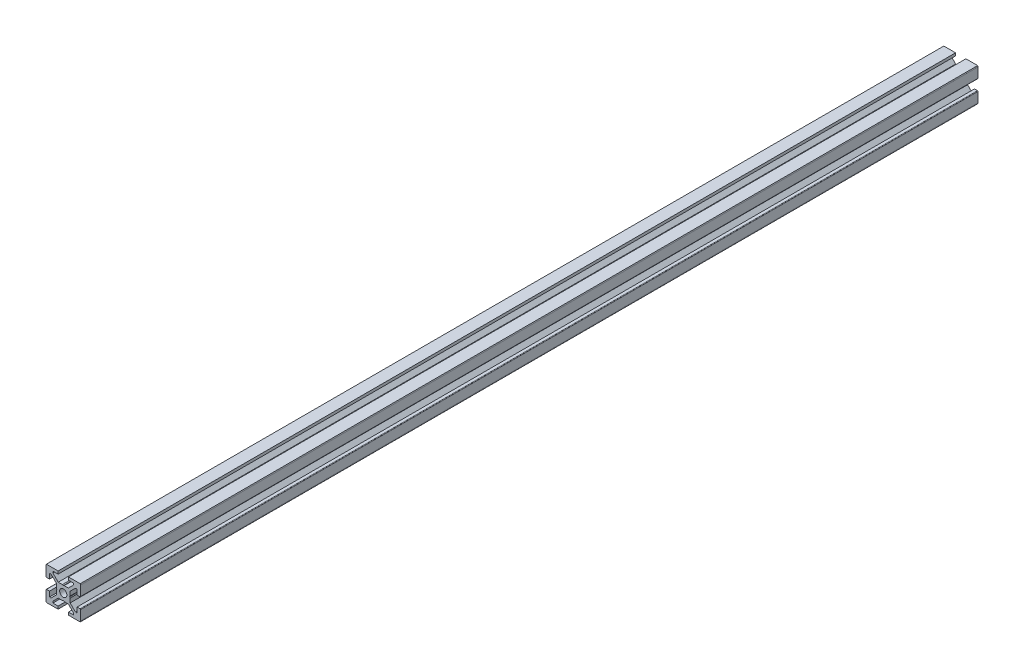
SolidWorks part; units mm, degrees
ref_plane "前视基准面" through (0, 0, 0) normal (0, 0, 1) x (1, 0, 0)
ref_plane "上视基准面" through (0, 0, 0) normal (0, 1, 0) x (1, 0, 0)
ref_plane "右视基准面" through (0, 0, 0) normal (1, 0, 0) x (0, 0, -1)
sketch "草图3" plane through (0, 0, 0) normal (0, 0, 1) x (1, 0, 0)
  line L0 (50, 62.1) -> (50, 37.9) construction
  line L1 (57.0607, 56) -> (54, 52.9393)
  line L2 (58, 56) -> (58, 53)
  line L3 (56, 57.0607) -> (52.9393, 54)
  line L4 (42, 56) -> (42, 53)
  line L5 (42.9393, 56) -> (46, 52.9393)
  line L6 (44, 57.0607) -> (47.0607, 54)
  line L7 (60, 59) -> (60, 53.3)
  line L8 (40, 59) -> (40, 53.3)
  line L9 (37.5, 50) -> (62.5, 50) construction
  line L10 (57.0607, 44) -> (54, 47.0607)
  line L11 (53, 40.4) -> (59.8, 40.4)
  line L12 (42.9393, 44) -> (46, 47.0607)
  line L13 (44, 42) -> (47, 42)
  line L14 (44, 42.9393) -> (47.0607, 46)
  line L15 (40.2, 40.4) -> (47, 40.4)
  line L16 (42, 44) -> (42, 47)
  line L17 (44, 42.9393) -> (44, 42)
  line L18 (40, 46.7) -> (40, 41)
  line L19 (42, 44) -> (42.9393, 44)
  line L20 (40.3, 47) -> (42, 47)
  line L21 (40.3, 53) -> (42, 53)
  line L22 (47, 40.4) -> (47, 42)
  line L23 (56, 42.9393) -> (56, 42)
  line L24 (56, 42) -> (53, 42)
  line L25 (53, 40.4) -> (53, 42)
  line L26 (56, 42.9393) -> (52.9393, 46)
  line L27 (58, 44) -> (58, 47)
  line L28 (60, 46.7) -> (60, 41)
  line L29 (57.0607, 44) -> (58, 44)
  line L30 (59.7, 47) -> (58, 47)
  line L31 (59.7, 53) -> (58, 53)
  line L32 (53, 59.6) -> (59.8, 59.6)
  line L33 (44, 58) -> (47, 58)
  line L34 (40.2, 59.6) -> (47, 59.6)
  line L35 (42, 56) -> (42.9393, 56)
  line L36 (44, 58) -> (44, 57.0607)
  line L37 (47, 59.6) -> (47, 58)
  line L38 (53, 59.6) -> (53, 58)
  line L39 (56, 58) -> (53, 58)
  line L40 (56, 58) -> (56, 57.0607)
  line L41 (57.0607, 56) -> (58, 56)
  line L45 (46, 52.9393) -> (46, 50.5196)
  line L46 (54, 52.9393) -> (54, 50.5196)
  line L47 (47.0607, 54) -> (49.4804, 54)
  line L48 (47.0607, 46) -> (49.4804, 46)
  line L49 (50, 53.7) -> (49.4804, 54)
  line L50 (50, 53.7) -> (50.5196, 54)
  line L51 (50.5196, 54) -> (52.9393, 54)
  line L52 (46.3, 50) -> (46, 49.4804)
  line L53 (46.3, 50) -> (46, 50.5196)
  line L54 (50, 46.3) -> (50.5196, 46)
  line L55 (50, 46.3) -> (49.4804, 46)
  line L56 (53.7, 50) -> (54, 50.5196)
  line L57 (53.7, 50) -> (54, 49.4804)
  line L58 (54, 49.4804) -> (54, 47.0607)
  line L59 (50.5196, 46) -> (52.9393, 46)
  line L60 (46, 49.4804) -> (46, 47.0607)
  arc A0 (40.3, 47) -> (40, 46.7) centre (40.3, 46.7) ccw
  arc A1 (40, 53.3) -> (40.3, 53) centre (40.3, 53.3) ccw
  circle A2 centre (50, 50) radius 2.1
  arc A3 (60, 46.7) -> (59.7, 47) centre (59.7, 46.7) ccw
  arc A4 (59.7, 53) -> (60, 53.3) centre (59.7, 53.3) ccw
  arc A5 (60, 59) -> (59.8, 59.6) centre (59, 59) ccw
  arc A6 (40.2, 59.6) -> (40, 59) centre (41, 59) ccw
  arc A7 (40, 41) -> (40.2, 40.4) centre (41, 41) ccw
  arc A8 (59.8, 40.4) -> (60, 41) centre (59, 41) ccw
extrude "凸台-拉伸1" add sketch "草图3" along normal blind 520
